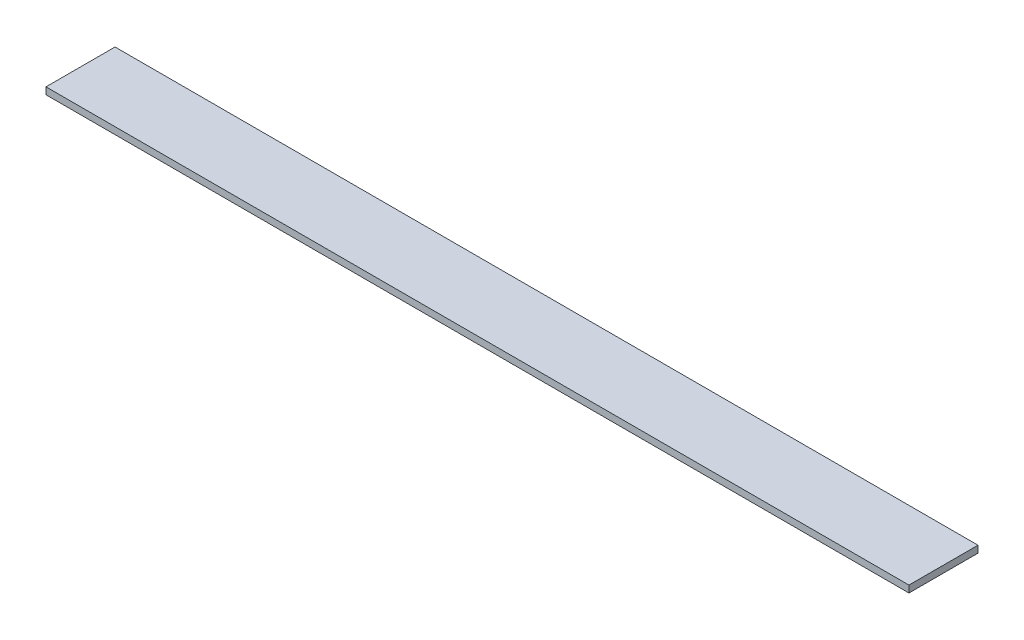
SolidWorks part; units mm, degrees
ref_plane "Front Plane" through (0, 0, 0) normal (0, 0, 1) x (1, 0, 0)
ref_plane "Top Plane" through (0, 0, 0) normal (0, 1, 0) x (1, 0, 0)
ref_plane "Right Plane" through (0, 0, 0) normal (1, 0, 0) x (0, 0, -1)
sketch "Эскиз1" plane through (0, 0, 0) normal (0, 1, 0) x (1, 0, 0)
  line L1 (0, 0) -> (500, 0)
  line L2 (0, 0) -> (0, 40)
  line L3 (0, 40) -> (500, 40)
  line L4 (500, 0) -> (500, 40)
  dimension "D1" = 500
  dimension "D2" = 40
extrude "Бобышка-Вытянуть1" add sketch "Эскиз1" along normal blind 4
